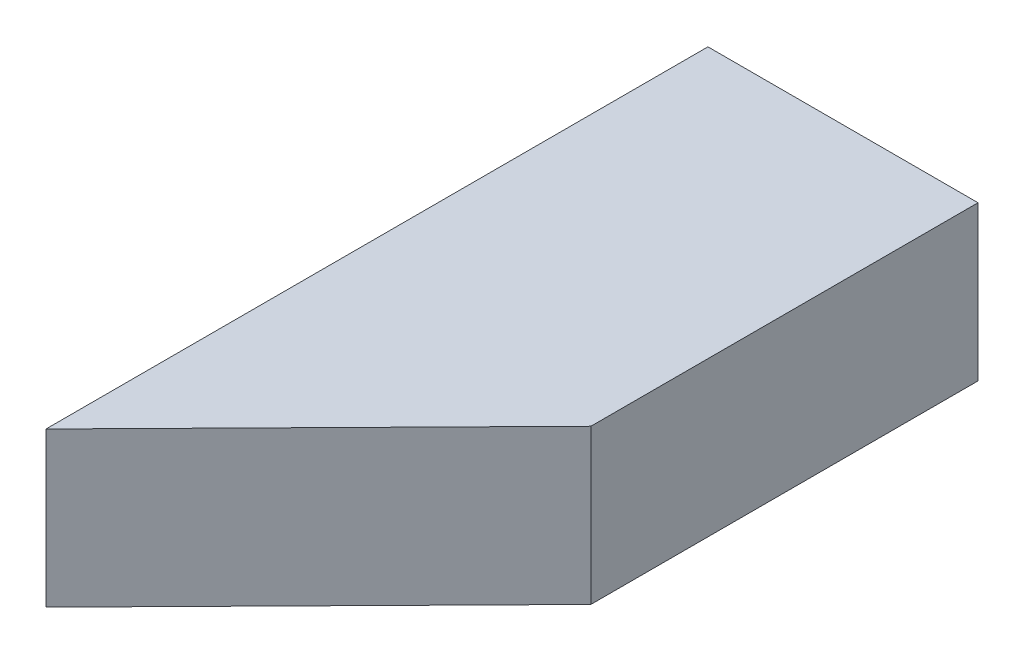
SolidWorks part; units mm, degrees
material "Pine"
ref_plane "X-Y Datum" through (0, 0, 0) normal (0, 0, 1) x (1, 0, 0)
ref_plane "X-Z Datum" through (0, 0, 0) normal (0, 1, 0) x (1, 0, 0)
ref_plane "Y-Z Datum" through (0, 0, 0) normal (1, 0, 0) x (0, 0, -1)
sketch "Sketch2" plane through (0, 0, 0) normal (0, 0, 1) x (1, 0, 0)
  line L1 (0, 0) -> (88.9, 0)
  line L2 (0, 0) -> (0, 50.8)
  line L3 (0, 50.8) -> (88.9, 50.8)
  line L4 (88.9, 0) -> (88.9, 50.8)
  dimension "D1" = 88.9
  dimension "D2" = 50.8
extrude "Boss-Extrude1" add sketch "Sketch2" along normal blind 127.4295
sketch "Sketch3" plane through (0, 50.8, 0) normal (0, 1, 0) x (1, 0, 0)
  line L0 (0, -127.4295) -> (0, -217.8948)
  line L1 (0, -217.8948) -> (88.9, -127.4295)
  line L2 (88.9, -127.4295) -> (0, -127.4295)
  point P5 (0, -228.2616)
  dimension "D1" = 45.5
extrude "Boss-Extrude2" add sketch "Sketch3" against normal up to surface (50.8 mm away) up to face at (44.45, 0, 63.7148)
